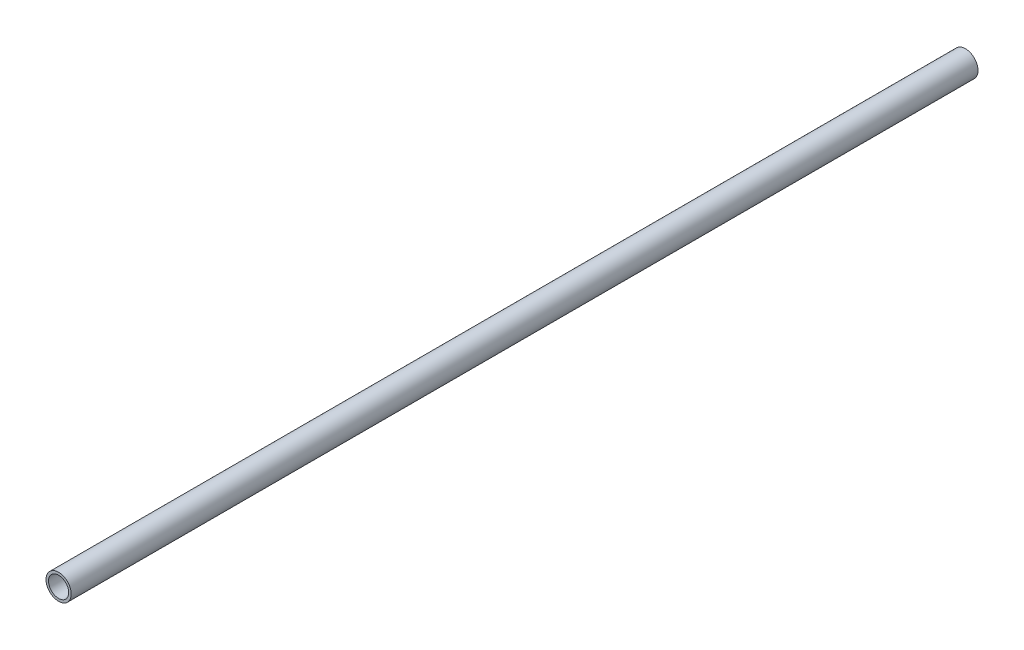
SolidWorks part; units mm, degrees
material "Thornel Mat VMA"
ref_plane "前视基准面" through (0, 0, 0) normal (0, 0, 1) x (1, 0, 0)
ref_plane "上视基准面" through (0, 0, 0) normal (0, 1, 0) x (1, 0, 0)
ref_plane "右视基准面" through (0, 0, 0) normal (1, 0, 0) x (0, 0, -1)
sketch "草图1" plane through (0, 0, 0) normal (0, 0, 1) x (1, 0, 0)
  circle A0 centre (0, 0) radius 4
  circle A1 centre (0, 0) radius 5
extrude "凸台-拉伸1" add sketch "草图1" along normal blind 360
